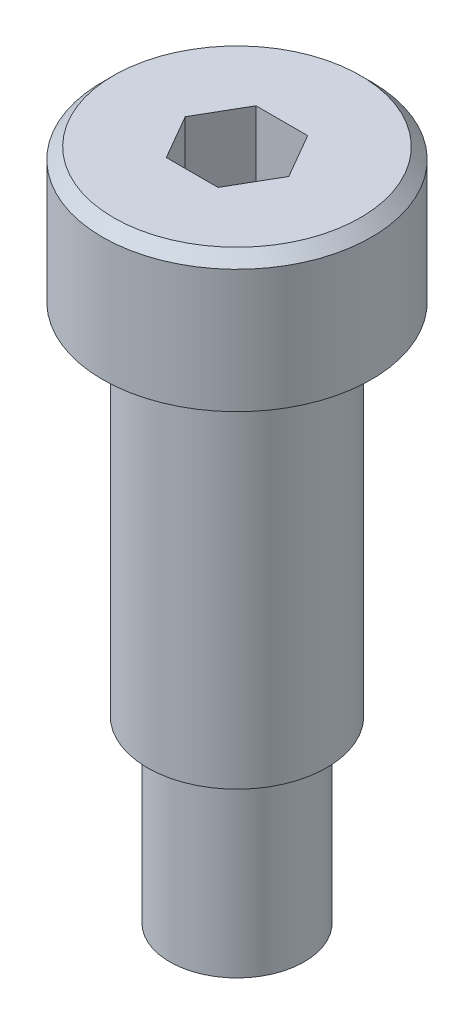
SolidWorks part; units mm, degrees
material "AISI 304"
ref_plane "Front Plane" through (0, 0, 0) normal (0, 0, 1) x (1, 0, 0)
ref_plane "Top Plane" through (0, 0, 0) normal (0, 1, 0) x (1, 0, 0)
ref_plane "Right Plane" through (0, 0, 0) normal (1, 0, 0) x (0, 0, -1)
sketch "Sketch1" plane through (0, 0, 0) normal (0, 1, 0) x (1, 0, 0)
  circle A0 centre (0, 0) radius 3
  dimension "D1" = 6
extrude "Boss-Extrude1" add sketch "Sketch1" along normal blind 3
sketch "Sketch2" plane through (0, 0, 0) normal (0, -1, 0) x (1, 0, 0)
  circle A0 centre (0, 0) radius 2
  dimension "D1" = 4
extrude "Boss-Extrude2" add sketch "Sketch2" along normal blind 8
sketch "Sketch3" plane through (0, -8, 0) normal (0, -1, 0) x (1, 0, 0)
  circle A0 centre (0, 0) radius 1.5
  dimension "D1" = 3
extrude "Boss-Extrude3" add sketch "Sketch3" along normal blind 4
cosmetic thread "Cosmetic Thread1" parameters "D2"=2.439
sketch "Sketch4" plane through (0, 3, 0) normal (0, 1, 0) x (1, 0, 0)
  line L1 (0.5774, 1) -> (-0.5774, 1)
  line L2 (-0.5774, 1) -> (-1.1547, 0)
  line L3 (-1.1547, 0) -> (-0.5774, -1)
  line L4 (-0.5774, -1) -> (0.5774, -1)
  line L5 (0.5774, -1) -> (1.1547, 0)
  line L6 (1.1547, 0) -> (0.5774, 1)
  circle A0 centre (0, 0) radius 1 construction
  dimension "D1" = 2
extrude "Cut-Extrude1" cut sketch "Sketch4" against normal blind 2
chamfer "Chamfer1" distance 0.25 angle 45 1 edges at (0, 3, 3)
